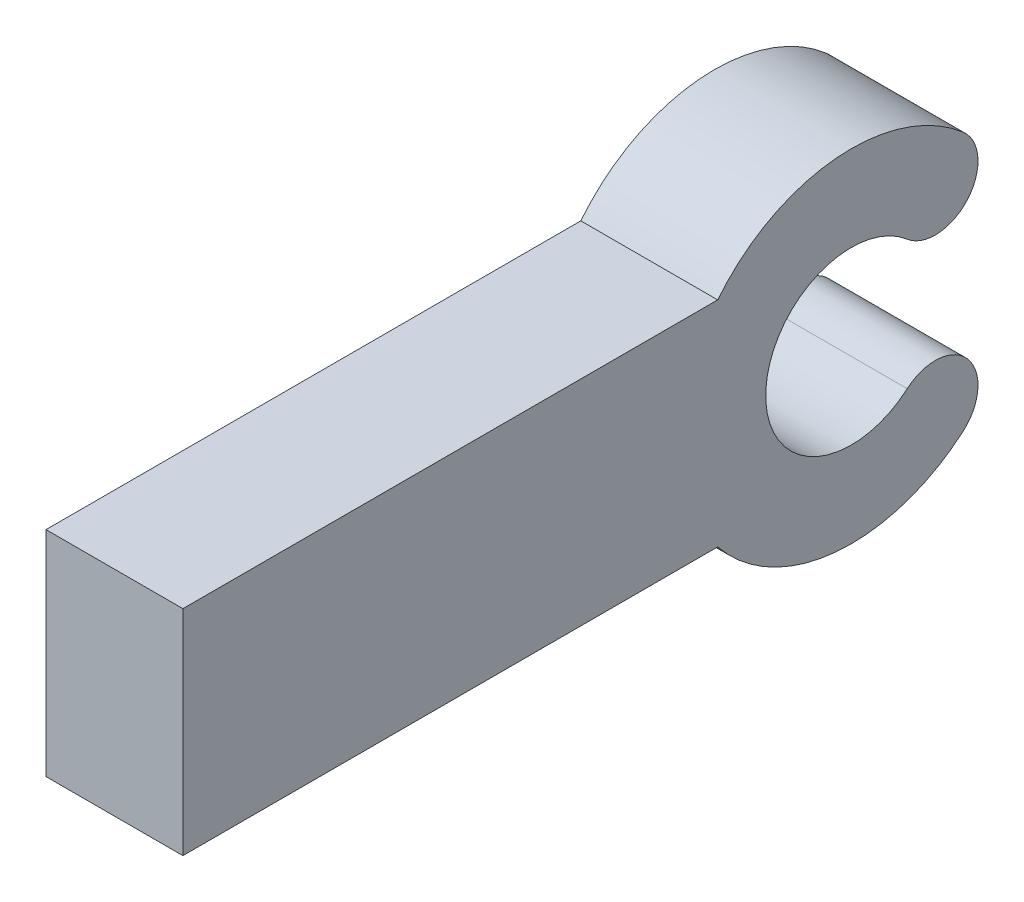
SolidWorks part; units mm, degrees
material "Delrin 2700 NC010, Low Viscosity Acetal Copolymer (SS)"
ref_plane "Front Plane" through (0, 0, 0) normal (0, 0, 1) x (1, 0, 0)
ref_plane "Top Plane" through (0, 0, 0) normal (0, 1, 0) x (1, 0, 0)
ref_plane "Right Plane" through (0, 0, 0) normal (1, 0, 0) x (0, 0, -1)
sketch "Sketch1" plane through (0, 0, 0) normal (1, 0, 0) x (0, 0, -1)
  line L0 (0, 1.27) -> (10.4547, 1.27) construction
  line L1 (0, 0) -> (6.35, 0)
  line L2 (0, 0) -> (0, 2.54)
  line L3 (0, 2.54) -> (6.35, 2.54)
  arc A0 (9.2652, 2.8072) -> (6.35, 2.54) centre (7.9362, 1.27) ccw
  arc A1 (8.6007, 2.0386) -> (8.6007, 0.5014) centre (7.9362, 1.27) ccw
  arc A2 (9.2652, 2.8072) -> (8.6007, 2.0386) centre (8.9329, 2.4229) cw
  arc A3 (8.6007, 0.5014) -> (9.2652, -0.2672) centre (8.9329, 0.1171) cw
  arc A4 (6.35, 0) -> (9.2652, -0.2672) centre (7.9362, 1.27) ccw
  dimension "D3" = 2.032
  dimension "D4" = 4.064
  dimension "D1" = 2.54
  dimension "D2" = 6.35
extrude "Boss-Extrude1" add sketch "Sketch1" along normal blind 1.6256
